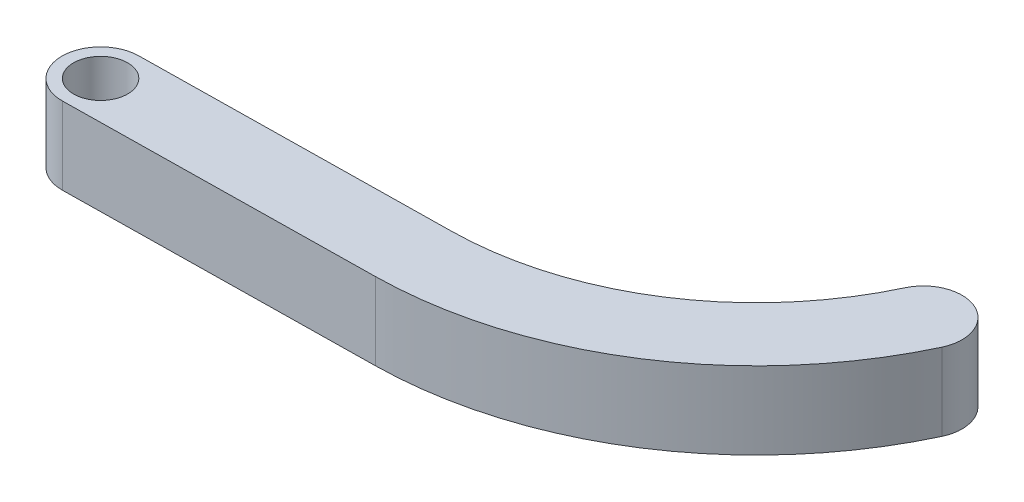
SolidWorks part; units mm, degrees
ref_plane "Front Plane" through (0, 0, 0) normal (0, 0, 1) x (1, 0, 0)
ref_plane "Top Plane" through (0, 0, 0) normal (0, 1, 0) x (1, 0, 0)
ref_plane "Right Plane" through (0, 0, 0) normal (1, 0, 0) x (0, 0, -1)
sketch "Sketch1" plane through (0, 0, 0) normal (0, 1, 0) x (1, 0, 0)
  line L4 (-0.0461, 3.1747) -> (25.3078, 3.5428)
  line L7 (0.0461, -3.1747) -> (25.4, -2.8066)
  circle A2 centre (0, 0) radius 2.2225
  arc A3 (-0.0461, 3.1747) -> (0.0461, -3.1747) centre (0, 0) ccw
  arc A6 (53.6734, 15.4345) -> (47.9266, 18.1356) centre (50.8, 16.785) ccw
  arc A7 (25.3078, 3.5428) -> (47.9266, 18.1356) centre (24.9391, 28.9401) ccw
  arc A8 (25.4, -2.8066) -> (53.6734, 15.4345) centre (24.9391, 28.9401) ccw
  point P1 (54.1113, 20.7492)
  point P4 (44.5468, 3.1741)
  point P6 (23.2288, -3.175)
  point P13 (48.6736, 12.0646)
  point P14 (24.4561, 2.5005)
  point P16 (53.3044, 35.1163)
  point P17 (51.7049, 20.7825)
  point P18 (24.7512, 2.4415)
  point P19 (51.8279, 19.5609)
  point P20 (52, 19.7621)
  dimension "D2" = 50.8
  dimension "D3" = 4.445
  dimension "D1" = 6.35
  dimension "D4" = 63.5
  dimension "D5" = 25.4
  dimension "D6" = 50.8
extrude "Boss-Extrude1" add sketch "Sketch1" along normal blind 6.35
